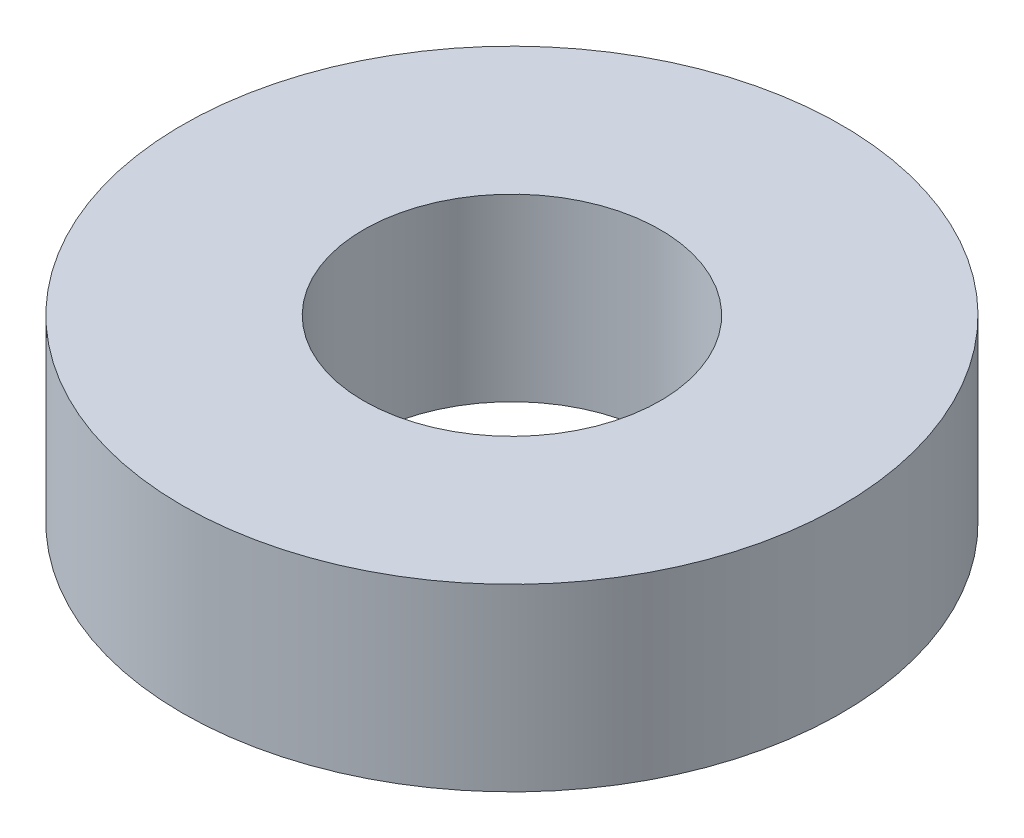
SolidWorks part; units mm, degrees
material "Galvanized Steel"
ref_plane "Front Plane" through (0, 0, 0) normal (0, 0, 1) x (1, 0, 0)
ref_plane "Top Plane" through (0, 0, 0) normal (0, 1, 0) x (1, 0, 0)
ref_plane "Right Plane" through (0, 0, 0) normal (1, 0, 0) x (0, 0, -1)
sketch "Sketch1" plane through (0, 0, 0) normal (0, 1, 0) x (1, 0, 0)
  circle A0 centre (0, 0) radius 11
  circle A1 centre (0, 0) radius 4.95
  dimension "D1" = 22
  dimension "D2" = 9.9
extrude "Boss-Extrude1" add sketch "Sketch1" along normal blind 6
